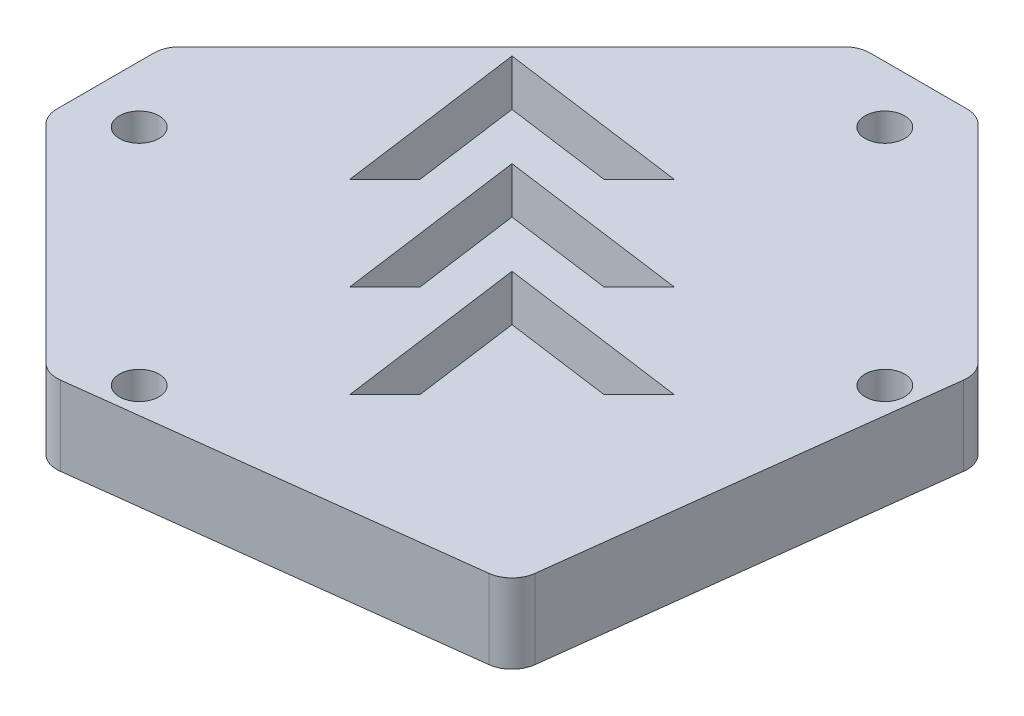
SolidWorks part; units mm, degrees
material "PET"
ref_plane "Front Plane" through (0, 0, 0) normal (0, 0, 1) x (1, 0, 0)
ref_plane "Top Plane" through (0, 0, 0) normal (0, 1, 0) x (1, 0, 0)
ref_plane "Right Plane" through (0, 0, 0) normal (1, 0, 0) x (0, 0, -1)
other "Configuration Table"
sketch "草图1" plane through (0, 0, 0) normal (0, 1, 0) x (1, 0, 0)
  line L1 (-30, 32.5) -> (30, 32.5)
  line L2 (-30, 32.5) -> (-30, -32.5)
  line L3 (-30, -32.5) -> (30, -32.5)
  line L4 (30, 32.5) -> (30, -32.5)
  line L5 (-30, 32.5) -> (30, -32.5) construction
  line L6 (-30, -32.5) -> (30, 32.5) construction
  point P0 (0, 0)
  dimension "D1" = 65
  dimension "D2" = 60
extrude "凸台-拉伸1" add sketch "草图1" along normal blind 6
sketch "草图2" plane through (0, 6, 0) normal (0, 1, 0) x (1, 0, 0)
  line L0 (-21.5, 21.5) -> (13.2745, -13.2745) construction
  line L1 (-30, 32.5) -> (-30, -32.5) construction
  dimension "D1" = 45
sketch "草图4" plane through (0, 6, 0) normal (0, 1, 0) x (1, 0, 0)
  line L0 (8.6748, 28.1827) -> (-19.6095, -0.1016) construction
  line L1 (-141442.8562, 141442.8562) -> (141434.6307, -141434.6307) construction
  line L2 (-2.639, -17.0722) -> (-19.6095, -0.1016) construction
  line L3 (8.6748, 28.1827) -> (25.6453, 11.2121) construction
  circle A0 centre (-19.6095, -0.1016) radius 1.5
  circle A1 centre (8.6748, 28.1827) radius 1.5
  circle A2 centre (-2.639, -17.0722) radius 1.5
  circle A3 centre (25.6453, 11.2121) radius 1.5
  dimension "D4" = 3
  dimension "D1" = 40
  dimension "D2" = 24
  dimension "D3" = 24
extrude "切除-拉伸1" cut sketch "草图4" against normal blind 8
sketch "草图5" plane through (0, 6, 0) normal (0, 1, 0) x (1, 0, 0)
  line L0 (8.6748, 28.1827) -> (-19.6095, -0.1016) construction
  line L1 (-10.1401, 18.7133) -> (22.1788, -13.6057) construction
  line L2 (-10.1401, 18.7133) -> (-8.1899, 4.45)
  line L3 (-8.1899, 4.45) -> (-5.5262, 7.1137)
  line L4 (-5.5262, 7.1137) -> (-6.6326, 15.2058)
  line L5 (-6.6326, 15.2058) -> (1.4594, 14.0993)
  line L6 (1.4594, 14.0993) -> (4.1231, 16.763)
  line L7 (4.1231, 16.763) -> (-10.1401, 18.7133)
  line L8 (11.1942, 9.692) -> (-3.0691, 11.6422)
  line L9 (-3.0691, 11.6422) -> (-1.1188, -2.621)
  line L10 (-1.1188, -2.621) -> (1.5449, 0.0427)
  line L11 (1.5449, 0.0427) -> (0.4384, 8.1347)
  line L12 (0.4384, 8.1347) -> (8.5305, 7.0283)
  line L13 (8.5305, 7.0283) -> (11.1942, 9.692)
  line L14 (18.2653, 2.6209) -> (4.002, 4.5711)
  line L15 (4.002, 4.5711) -> (5.9522, -9.6921)
  line L16 (5.9522, -9.6921) -> (8.6159, -7.0284)
  line L17 (8.6159, -7.0284) -> (7.5095, 1.0636)
  line L18 (7.5095, 1.0636) -> (15.6016, -0.0428)
  line L19 (15.6016, -0.0428) -> (18.2653, 2.6209)
  point P15 (-5.4674, 14.0405)
  dimension "D1" = 3
  dimension "D2" = 3
  dimension "D3" = 3
extrude "切除-拉伸2" cut sketch "草图5" against normal blind 8
sketch "草图6" plane through (0, 6, 0) normal (0, 1, 0) x (1, 0, 0)
  line L0 (-25, -32.5) -> (-25, 56.0414) construction
  line L2 (-30, 32.5) -> (-30, -32.5) construction
  dimension "D1" = 5
sketch "草图7" plane through (0, 6, 0) normal (0, 1, 0) x (1, 0, 0)
  line L0 (-25, -200032.5) -> (-25, 200056.0414) construction
  line L1 (-30, -32.5) -> (30, -32.5) construction
  line L2 (-30, 0) -> (53.9878, 0) construction
  circle A0 centre (-21, -24.5) radius 1.5
  circle A1 centre (-21, -16.5) radius 1.5
  circle A2 centre (-21, 24.5) radius 1.5
  circle A3 centre (-21, 16.5) radius 1.5
  dimension "D2" = 3
  dimension "D3" = 3
  dimension "D1" = 4
  dimension "D4" = 8
  dimension "D5" = 8
extrude "切除-拉伸3" cut sketch "草图7" against normal blind 8
sketch "草图8" plane through (0, 6, 0) normal (0, 1, 0) x (1, 0, 0)
  line L1 (11.4285, 32.5) -> (28.3991, 15.5294)
  line L8 (24.5327, -15.9595) -> (28.3991, 15.5294)
  line L9 (-10.1206, 18.6938) -> (7.5047, 1.0685) construction
  line L10 (30, 32.5) -> (-30, 32.5) construction
  line L11 (11.4285, 32.5) -> (2.4285, 32.5)
  line L12 (2.4285, 32.5) -> (-23.9268, 6.1447)
  line L14 (24.5327, -15.9595) -> (-6.9563, -19.8259)
  line L15 (-23.9268, -2.8553) -> (-6.9563, -19.8259)
  line L16 (-23.9268, -2.8553) -> (-23.9268, 6.1447)
  line L21 (30, -32.5) -> (30, 32.5)
  line L22 (30, 32.5) -> (-30, 32.5)
  line L23 (-30, 32.5) -> (-30, -32.5)
  line L24 (-30, -32.5) -> (30, -32.5)
  line L25 (30, -32.5) -> (30, 32.5)
  line L26 (30, 32.5) -> (-30, 32.5)
  line L27 (-30, 32.5) -> (-30, -32.5)
  line L28 (-30, -32.5) -> (30, -32.5)
  circle A0 centre (25.6453, 11.2121) radius 1.5 construction
  point P18 (-10.7492, 19.3223)
  circle M16 centre (-21, -24.5) radius 1.5
  circle M17 centre (-21, 16.5) radius 1.5
  circle M18 centre (-21, 24.5) radius 1.5
  circle M19 centre (-21, -16.5) radius 1.5
  line M42 (30, -32.5) -> (30, 32.5)
  line M43 (30, 32.5) -> (-30, 32.5)
  line M44 (-30, 32.5) -> (-30, -32.5)
  line M45 (-30, -32.5) -> (30, -32.5)
  dimension "D3" = 5
  dimension "D4" = 9
  dimension "D1" = 24
  dimension "D2" = 52
  dimension "D5" = 0
extrude "切除-拉伸4" cut sketch "草图8" against normal blind 10 contours L9 L12 M43 | L9 L26 L14 L15 L16 L12 M44 M45 M42 M16 M18 M19 M17 | L8 L9 L25 L1 M43
fillet "圆角1" radius 2 7 edges at (-23.9268, 3, -6.1447) (-23.9268, 3, 2.8553) (24.5327, 3, 15.9595) (28.3991, 3, -15.5294) (11.4285, 3, -32.5) (2.4285, 3, -32.5) (-6.9563, 3, 19.8259)
